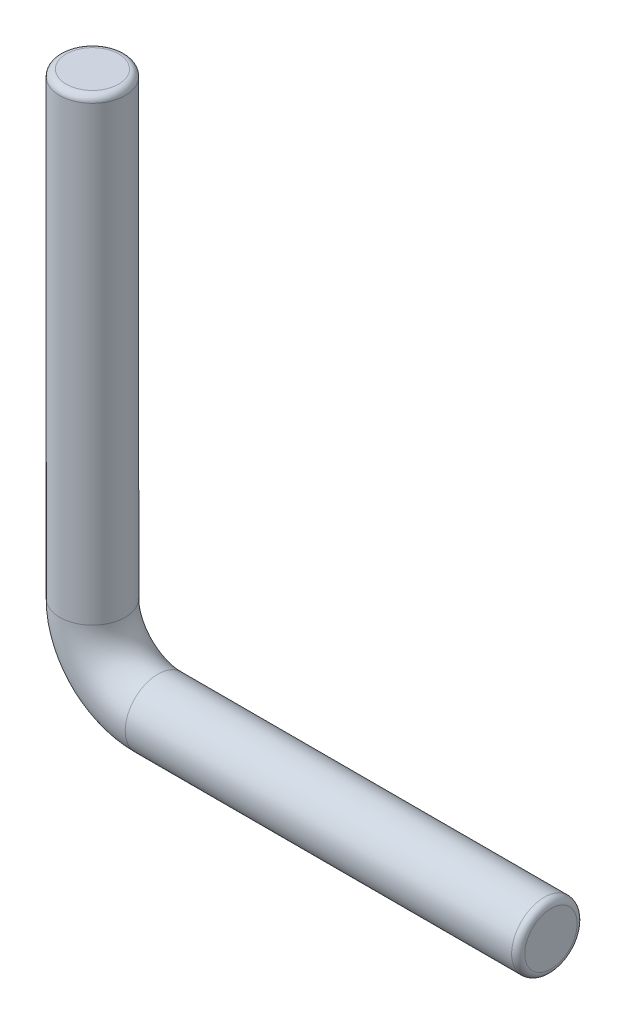
SolidWorks part; units mm, degrees
ref_plane "Front Plane" through (0, 0, 0) normal (0, 0, 1) x (1, 0, 0)
ref_plane "Top Plane" through (0, 0, 0) normal (0, 1, 0) x (1, 0, 0)
ref_plane "Right Plane" through (0, 0, 0) normal (1, 0, 0) x (0, 0, -1)
sketch "Sketch1" plane through (0, 0, 0) normal (0, 0, 1) x (1, 0, 0)
  line L0 (10, 0) -> (70, 0)
  line L1 (0, 10) -> (0, 80)
  arc A0 (10, 0) -> (0, 10) centre (10, 10) cw
  point P6 (0, 0)
  dimension "D3" = 10
  dimension "D1" = 70
  dimension "D2" = 80
sweep "Sweep1" add path "Sketch1" circular profile diameter 10 parameters "D3"=10
fillet "Fillet1" radius 1 2 edges at (70, 0, -5) (0, 80, -5)
